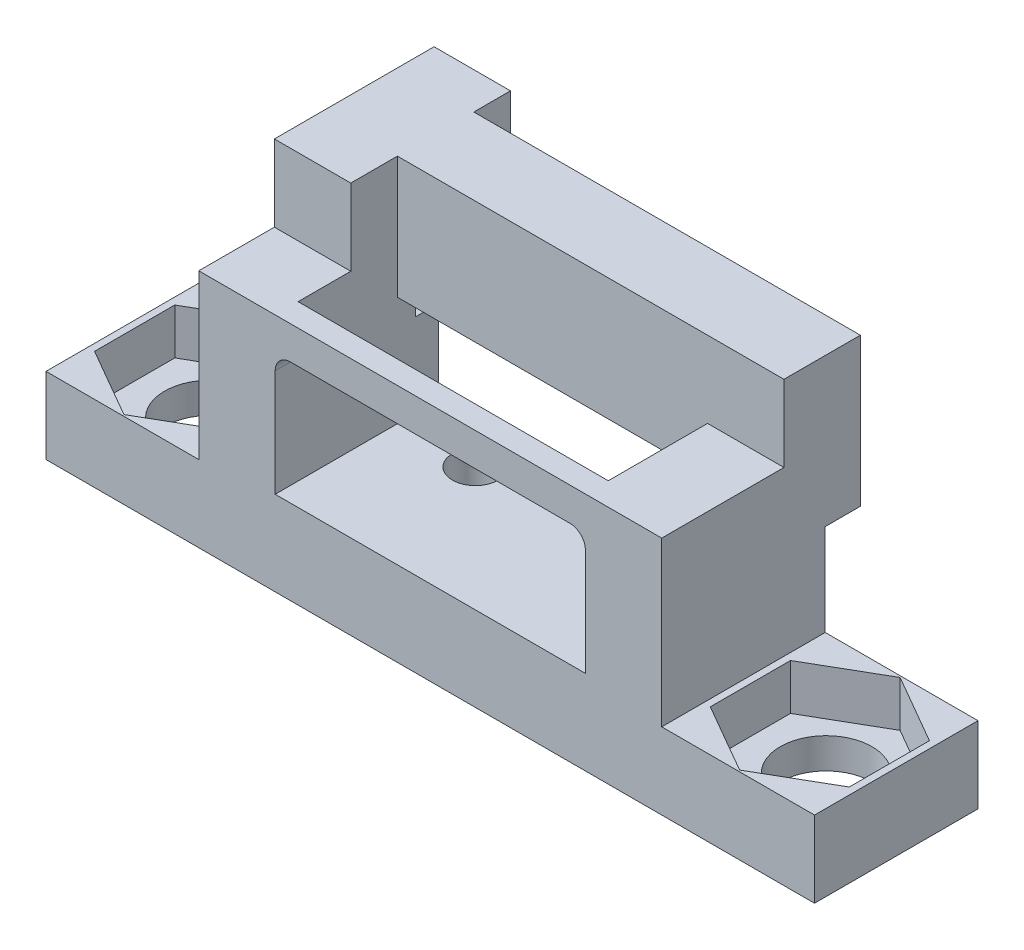
SolidWorks part; units mm, degrees
ref_plane "Alzado" through (0, 0, 0) normal (0, 0, 1) x (1, 0, 0)
ref_plane "Planta" through (0, 0, 0) normal (0, 1, 0) x (1, 0, 0)
ref_plane "Vista lateral" through (0, 0, 0) normal (1, 0, 0) x (0, 0, -1)
sketch "Croquis1" plane through (0, 0, 0) normal (0, 1, 0) x (1, 0, 0)
  line L1 (0, 0) -> (-50.3, 0)
  line L2 (0, 0) -> (0, -10.7)
  line L3 (0, -10.7) -> (-50.3, -10.7)
  line L4 (-50.3, 0) -> (-50.3, -10.7)
  dimension "D1" = 10.7
  dimension "D2" = 50.3
extrude "Saliente-Extruir1" add sketch "Croquis1" along normal blind 15.7
sketch "Croquis2" plane through (0, 0, 10.7) normal (0, 0, 1) x (1, 0, 0)
  line L0 (-50.3, 5) -> (-40.3, 5)
  line L1 (-50.3, 15.7) -> (-50.3, 0) construction
  line L2 (-40.3, 5) -> (-40.3, 15.7)
  line L3 (-50.3, 15.7) -> (0, 15.7) construction
  line L4 (-25.15, 15.7) -> (-25.15, 10.6214) construction
  line L5 (-35.3, 5.5329) -> (-15, 5.5329)
  line L6 (-34.3, 13.5329) -> (-16, 13.5329)
  line L7 (-35.3, 12.5329) -> (-35.3, 5.5329)
  line L10 (0, 5) -> (-10, 5)
  line L11 (-10, 5) -> (-10, 15.7)
  line L12 (-15, 12.5329) -> (-15, 5.5329)
  line L13 (-50.3, 5) -> (-50.3, 15.7)
  line L14 (-50.3, 15.7) -> (-40.3, 15.7)
  line L15 (0, 5) -> (0, 15.7)
  line L16 (0, 15.7) -> (-10, 15.7)
  arc A0 (-15, 12.5329) -> (-16, 13.5329) centre (-16, 12.5329) ccw
  arc A1 (-34.3, 13.5329) -> (-35.3, 12.5329) centre (-34.3, 12.5329) ccw
  point P17 (-25.15, 5.5329)
  point P18 (-25.15, 13.5329)
  point P23 (-15, 13.5329)
  point P26 (-35.3, 13.5329)
  dimension "D5" = 1
  dimension "D1" = 10
  dimension "D2" = 10.7
  dimension "D3" = 8
  dimension "D4" = 10.15
extrude "Cortar-Extruir1" cut sketch "Croquis2" against normal up to next
sketch "Croquis3" plane through (0, 15.7, 0) normal (0, 1, 0) x (1, 0, 0)
  line L0 (-40.3, -5.35) -> (-35.3, -5.35) construction
  line L1 (-40.3, 0) -> (-40.3, -10.7) construction
  line L2 (-25.15, -10.7) -> (-25.15, -9.2) construction
  line L3 (-40.3, -10.7) -> (-10, -10.7) construction
  line L4 (-10, -5.35) -> (-15, -5.35) construction
  line L5 (-10, 0) -> (-10, -10.7) construction
  line L7 (-35.3, 0) -> (-15, 0)
  line L8 (-35.3, 0) -> (-35.3, -9.2)
  line L9 (-35.3, -9.2) -> (-15, -9.2)
  line L10 (-15, 0) -> (-15, -9.2)
  dimension "D1" = 1.5
  dimension "D2" = 5
  dimension "D3" = 5
extrude "Cortar-Extruir2" cut sketch "Croquis3" against normal up to next
sketch "Croquis4" plane through (-40.3, 0, 0) normal (-1, 0, 0) x (0, 0, 1)
  line L7 (0, 15.7) -> (1.5, 15.7)
  line L8 (0, 15.7) -> (0, 11)
  line L9 (0, 11) -> (1.5, 11)
  line L10 (1.5, 15.7) -> (1.5, 11)
  dimension "D3" = 1.5
  dimension "D4" = 4.7
extrude "Cortar-Extruir3" cut sketch "Croquis4" against normal up to next
sketch "Croquis6" plane through (0, 5, 0) normal (0, 1, 0) x (1, 0, 0)
  line L0 (-45.3, 0) -> (-45.3, -4.9411) construction
  line L1 (-40.3, 0) -> (-50.3, 0) construction
  line L3 (-15, 0) -> (-35.3, 0) construction
  line L4 (-25.15, 0) -> (-25.15, -4.9411) construction
  circle A0 centre (-45.3, -4.9411) radius 3
  circle A1 centre (-5, -4.9411) radius 3
  dimension "D1" = 6
extrude "Cortar-Extruir5" cut sketch "Croquis6" against normal up to next contours A0 | A1
sketch "Croquis7" plane through (0, 5.5329, 0) normal (0, 1, 0) x (1, 0, 0)
  line L0 (-30.3, -10.7) -> (-30.3, -2.6) construction
  line L1 (-35.3, -10.7) -> (-15, -10.7) construction
  line L2 (-30.3, -2.6) -> (-35.3, -2.6) construction
  line L3 (-35.3, 0) -> (-35.3, -10.7) construction
  line L4 (-25.15, 0) -> (-25.15, -1.6024) construction
  line L5 (-15, 0) -> (-35.3, 0) construction
  circle A0 centre (-30.3, -2.6) radius 1.5
  circle A1 centre (-20, -2.6) radius 1.5
  dimension "D1" = 5
  dimension "D3" = 3
  dimension "D2" = 8.1
extrude "Cortar-Extruir6" cut sketch "Croquis7" against normal up to next
sketch "Croquis8" plane through (0, 5, 0) normal (0, 1, 0) x (1, 0, 0)
  line L0 (0, -5.35) -> (-5, -5.35) construction
  line L1 (0, 0) -> (0, -10.7) construction
  line L2 (-5, -5.35) -> (-5, -0.1) construction
  line L3 (-25.15, 0) -> (-25.15, -3.8053) construction
  line L4 (-5, -0.1) -> (-9.5466, -2.725)
  line L5 (-9.5466, -2.725) -> (-9.5466, -7.975)
  line L6 (-9.5466, -7.975) -> (-5, -10.6)
  line L7 (-5, -10.6) -> (-0.4534, -7.975)
  line L8 (-0.4534, -7.975) -> (-0.4534, -2.725)
  line L9 (-0.4534, -2.725) -> (-5, -0.1)
  line L10 (-15, 0) -> (-35.3, 0) construction
  line L11 (-45.3, -5.35) -> (-45.3, -0.1) construction
  line L12 (-50.3, -5.35) -> (-45.3, -5.35) construction
  line L13 (-49.8466, -2.725) -> (-45.3, -0.1)
  line L14 (-49.8466, -7.975) -> (-49.8466, -2.725)
  line L15 (-45.3, -10.6) -> (-49.8466, -7.975)
  line L16 (-40.7534, -7.975) -> (-45.3, -10.6)
  line L17 (-40.7534, -2.725) -> (-40.7534, -7.975)
  line L18 (-45.3, -0.1) -> (-40.7534, -2.725)
  circle A0 centre (-5, -5.35) radius 4.5466 construction
  circle A1 centre (-45.3, -5.35) radius 4.5466 construction
  dimension "D1" = 5.25
extrude "Cortar-Extruir7" cut sketch "Croquis8" against normal blind 3
sketch "Croquis9" plane through (-35.3, 0, 0) normal (1, 0, 0) x (0, 0, -1)
  line L0 (-1.5, 15.7) -> (2.7, 15.7)
  line L1 (2.7, 15.7) -> (2.7, 11)
  line L2 (2.7, 11) -> (4.7, 11)
  line L3 (4.7, 11) -> (4.7, 20.7)
  line L4 (4.7, 20.7) -> (-5.7531, 20.7)
  line L5 (-5.7531, 20.7) -> (-5.7531, 15.7)
  line L6 (-1.5, 15.7) -> (-9.2, 15.7) construction
  line L7 (-5.7531, 15.7) -> (-1.5, 15.7)
  dimension "D1" = 5
  dimension "D2" = 4.2
  dimension "D3" = 2
  dimension "D4" = 4.7
extrude "Saliente-Extruir2" add sketch "Croquis9" against normal blind 5
sketch "Croquis11" plane through (0, 0, 0) normal (0, 0, -1) x (-1, 0, 0)
  line L2 (15, 15.7) -> (15, 5.5329) construction
  line L3 (10, 15.7) -> (15, 15.7)
  line L4 (10, 15.7) -> (10, 11)
  line L5 (10, 11) -> (15, 11)
  line L6 (15, 15.7) -> (15, 11)
  dimension "D1" = 4.7
extrude "Saliente-Extruir3" add sketch "Croquis11" along normal blind 2.3
sketch "Croquis12" plane through (0, 15.7, 0) normal (0, 1, 0) x (1, 0, 0)
  line L4 (-15, 2.3) -> (-25, 2.3)
  line L6 (-25, 2.3) -> (-25, -2.7)
  line L7 (-25, -2.7) -> (-15, -2.7)
  line L13 (-15, -9.2) -> (-15, 2.3) construction
  line L14 (-15, -2.7) -> (-15, 2.3)
  dimension "D1" = 5
  dimension "D2" = 10
extrude "Saliente-Extruir5" add sketch "Croquis12" against normal blind 3
sketch "Croquis13" plane through (0, 15.7, 0) normal (0, 1, 0) x (1, 0, 0)
  line L0 (-10, 0) -> (-10, -10.7) construction
  line L1 (-25, 2.3) -> (-10, 2.3)
  line L2 (-25, 2.3) -> (-25, -2.7)
  line L3 (-25, -2.7) -> (-10, -2.7)
  line L4 (-10, 2.3) -> (-10, -2.7)
extrude "Saliente-Extruir6" add sketch "Croquis13" along normal up to surface (5 mm away) up to face at (-37.8, 20.7, 0.5266)
sketch "Croquis14" plane through (-25, 0, 0) normal (-1, 0, 0) x (0, 0, 1)
  line L4 (2.7, 12.7) -> (2.7, 20.7)
  line L5 (2.7, 20.7) -> (-2.3, 20.7)
  line L6 (-2.3, 20.7) -> (-2.3, 12.7)
  line L7 (-2.3, 12.7) -> (2.7, 12.7)
  line L8 (2.7, 12.7) -> (2.7, 20.7)
  line L9 (2.7, 20.7) -> (-2.3, 20.7)
  line L10 (-2.3, 20.7) -> (-2.3, 12.7)
  line L11 (-2.3, 12.7) -> (2.7, 12.7)
  dimension "D1" = 0
extrude "Saliente-Extruir7" add sketch "Croquis14" along normal up to surface (10.3 mm away) up to face at (-35.3, 13.1665, 2.8219)
